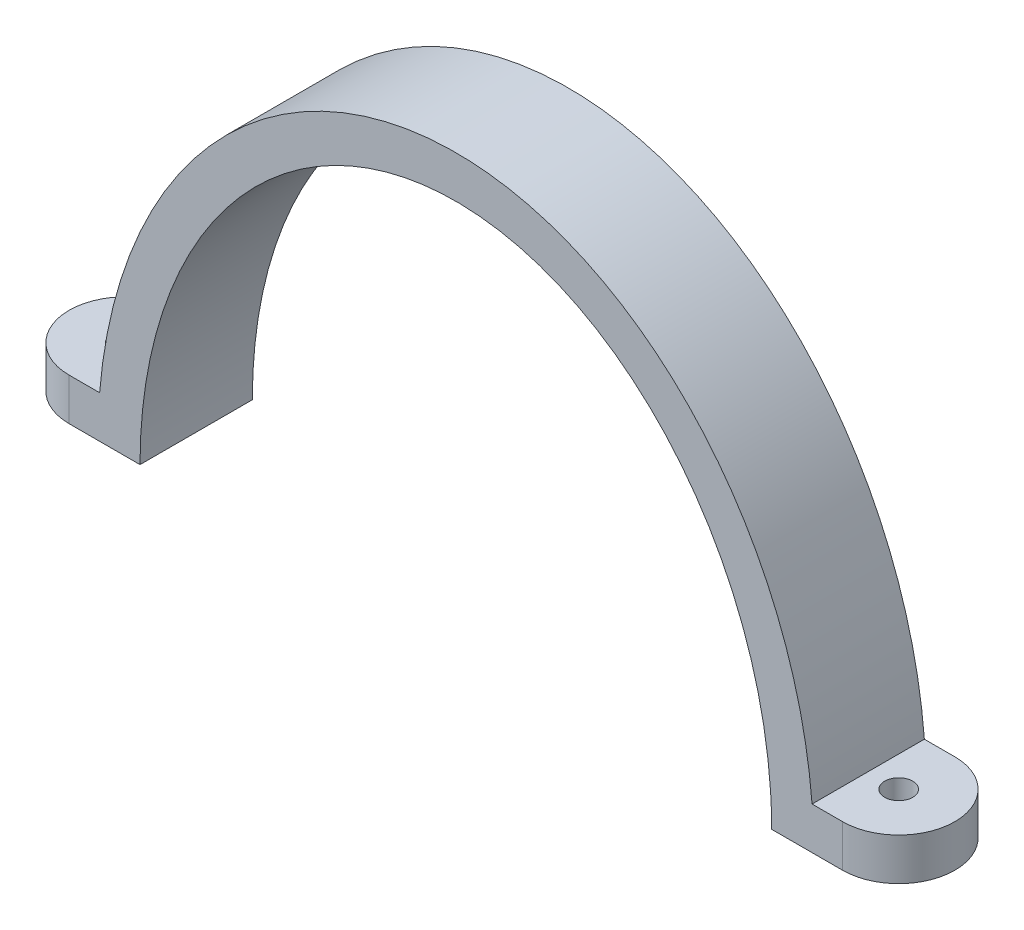
SolidWorks part; units mm, degrees
ref_plane "Front Plane" through (0, 0, 0) normal (0, 0, 1) x (1, 0, 0)
ref_plane "Top Plane" through (0, 0, 0) normal (0, 1, 0) x (1, 0, 0)
ref_plane "Right Plane" through (0, 0, 0) normal (1, 0, 0) x (0, 0, -1)
sketch "Sketch1" plane through (0, 0, 0) normal (0, 1, 0) x (1, 0, 0)
  line L0 (0, -4) -> (5, -4)
  line L1 (5, -4) -> (5, 4)
  line L2 (5, 4) -> (0, 4)
  line L3 (55.1, -4) -> (50.1, -4)
  line L4 (50.1, -4) -> (50.1, 4)
  line L5 (50.1, 4) -> (55.1, 4)
  circle A2 centre (0, 0) radius 1
  circle A3 centre (55.1, 0) radius 1
  arc A4 (0, 4) -> (0, -4) centre (0, 0) ccw
  arc A5 (55.1, -4) -> (55.1, 4) centre (55.1, 0) ccw
  arc A6 (0, -4) -> (0, 4) centre (0, 0) ccw construction
  circle A7 centre (0, 0) radius 4 construction
  arc A8 (55.1, 4) -> (55.1, -4) centre (55.1, 0) ccw construction
  circle A9 centre (55.1, 0) radius 4 construction
  dimension "D2" = 2
  dimension "D3" = 2
  dimension "D1" = 55.1
  dimension "D5" = 5
  dimension "D4" = 3
extrude "Boss-Extrude1" add sketch "Sketch1" along normal blind 3
sketch "Sketch2" plane through (0, 0, 0) normal (0, 0, 1) x (1, 0, 0)
  line L0 (1, 0) -> (54.1, 0) construction
  line L1 (2.05, 0) -> (5.05, 0)
  line L2 (50.05, 0) -> (53.05, 0)
  ellipse E0 centre (27.55, 0) end of major axis (27.55, 27.5) minor radius 22.5 (50.05, 0) -> (5.05, 0) ccw
  ellipse E1 centre (27.55, 0) end of major axis (27.55, 30.5) minor radius 25.5 (53.05, 0) -> (2.05, 0) ccw
  ellipse E2 centre (27.55, 0) end of major axis (27.55, 30.5) minor radius 25.5 (2.05, 0) -> (53.05, 0) ccw construction
  ellipse E3 centre (27.55, 0) end of major axis (27.55, 27.5) minor radius 22.5 (5.05, 0) -> (50.05, 0) ccw construction
  dimension "D1" = 55
  dimension "D2" = 45
  dimension "D3" = 3
  dimension "D4" = 3
extrude "Boss-Extrude2" add sketch "Sketch2" along normal mid plane 8
